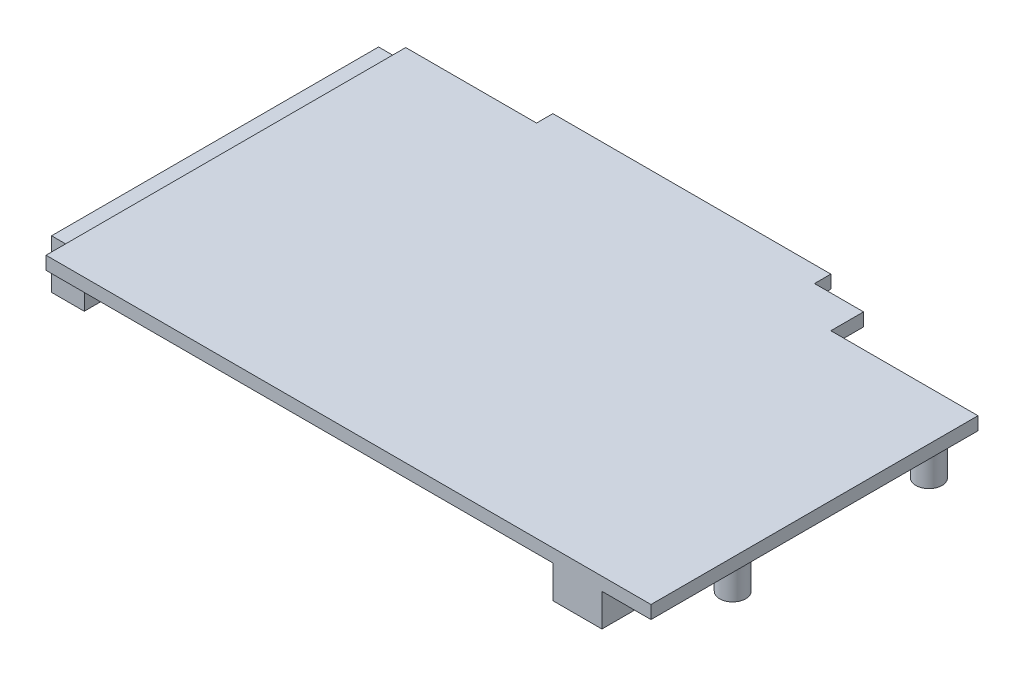
SolidWorks part; units mm, degrees
ref_plane "Front Plane" through (0, 0, 0) normal (0, 0, 1) x (1, 0, 0)
ref_plane "Top Plane" through (0, 0, 0) normal (0, 1, 0) x (1, 0, 0)
ref_plane "Right Plane" through (0, 0, 0) normal (1, 0, 0) x (0, 0, -1)
sketch "Sketch1" plane through (0, 0, 0) normal (0, 1, 0) x (1, 0, 0)
  line L1 (0, 0) -> (185, 0)
  line L2 (0, 0) -> (0, 100)
  line L3 (0, 100) -> (185, 100)
  line L4 (185, 0) -> (185, 100)
  dimension "D1" = 185
  dimension "D2" = 100
extrude "Boss-Extrude1" add sketch "Sketch1" along normal blind 4
sketch "Sketch2" plane through (0, 4, 0) normal (0, 1, 0) x (-1, 0, 0)
  line L0 (-185, -100) -> (0, -100) construction
  line L1 (-40, -100) -> (-125, -100)
  line L2 (-40, -100) -> (-40, -115)
  line L3 (-40, -115) -> (-125, -115)
  line L4 (-125, -100) -> (-125, -115)
  line L5 (-185, 0) -> (-185, -100) construction
  line L6 (-140, -100) -> (-140, -110)
  line L7 (0, -110) -> (-40, -110)
  line L8 (0, -100) -> (0, -110)
  line L9 (-140, -110) -> (-125, -110)
  line L10 (0, -100) -> (0, 0) construction
  line L11 (-185, 0) -> (-185, -100) construction
  line L12 (-185, -100) -> (0, -100) construction
  dimension "D1" = 60
  dimension "D2" = 85
  dimension "D3" = 15
  dimension "D4" = 45
  dimension "D5" = 10
extrude "Boss-Extrude2" add sketch "Sketch2" against normal blind 4
sketch "Sketch3" plane through (0, 0, 0) normal (0, -1, 0) x (1, 0, 0)
  line L0 (0, 0) -> (185, 0) construction
  line L1 (1.6993, -110) -> (-8.3007, -110)
  line L2 (1.6993, -110) -> (1.6993, -10)
  line L3 (1.6993, -10) -> (-8.3007, -10)
  line L4 (-8.3007, -110) -> (-8.3007, -10)
  line L5 (0, -110) -> (40, -110) construction
  dimension "D1" = 10
  dimension "D2" = 10
extrude "Boss-Extrude3" add sketch "Sketch3" along normal blind 15
sketch "Sketch4" plane through (0, 0, 0) normal (0, -1, 0) x (1, 0, 0)
  line L0 (185, -100) -> (140, -100) construction
  line L1 (127.6293, -20) -> (147.6293, -20)
  line L2 (127.6293, -20) -> (127.6293, -90)
  line L3 (127.6293, -90) -> (147.6293, -90)
  line L4 (147.6293, -20) -> (147.6293, -90)
  line L5 (0, 0) -> (185, 0) construction
  dimension "D1" = 20
  dimension "D2" = 10
  dimension "D3" = 20
extrude "Boss-Extrude4" add sketch "Sketch4" along normal blind 6
sketch "Sketch5" plane through (0, 0, 0) normal (0, -1, 0) x (1, 0, 0)
  line L0 (0, 0) -> (185, 0) construction
  line L1 (170, 0) -> (155, 0)
  line L2 (170, 0) -> (170, -20)
  line L3 (170, -20) -> (155, -20)
  line L4 (155, 0) -> (155, -20)
  line L5 (185, 0) -> (185, -100) construction
  dimension "D1" = 15
  dimension "D2" = 20
  dimension "D3" = 15
extrude "Boss-Extrude5" add sketch "Sketch5" along normal blind 10
sketch "Sketch6" plane through (0, 0, 0) normal (0, -1, 0) x (1, 0, 0)
  line L0 (180, -1023.0016) -> (180, 48976.9984) construction
  line L1 (185, 0) -> (185, -100) construction
  line L2 (170, 0) -> (185, 0) construction
  circle A0 centre (180, -30) radius 4
  circle A1 centre (180, -90) radius 4
  dimension "D2" = 8
  dimension "D1" = 5
  dimension "D3" = 30
  dimension "D4" = 60
extrude "Boss-Extrude6" add sketch "Sketch6" along normal blind 10
